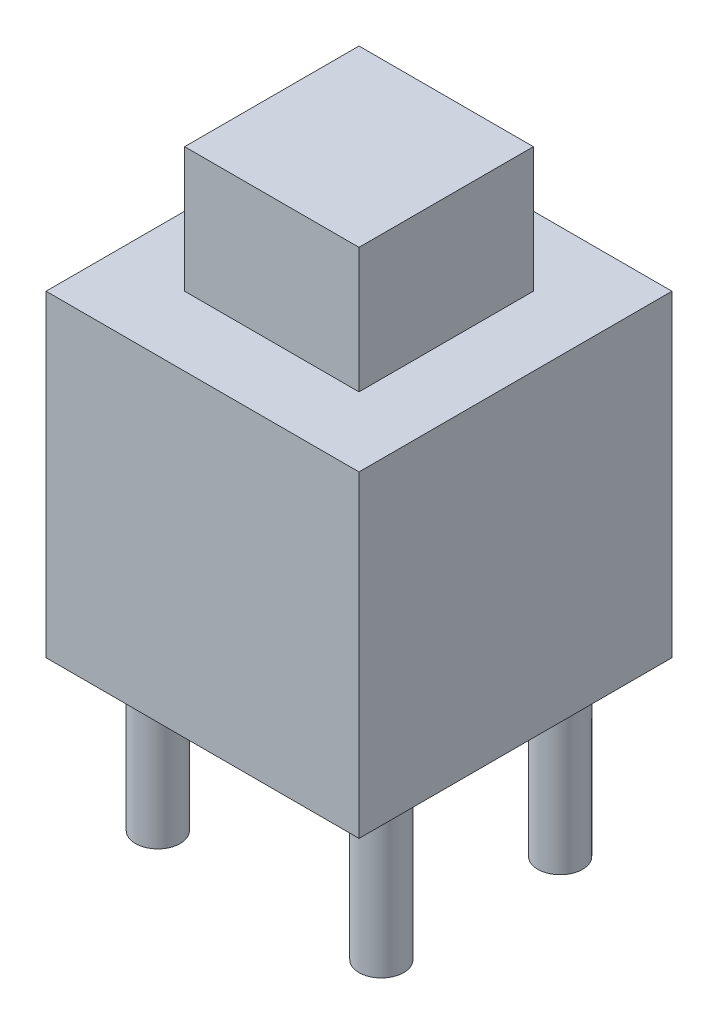
SolidWorks part; units mm, degrees
ref_plane "前视基准面" through (0, 0, 0) normal (0, 0, 1) x (1, 0, 0)
ref_plane "上视基准面" through (0, 0, 0) normal (0, 1, 0) x (1, 0, 0)
ref_plane "右视基准面" through (0, 0, 0) normal (1, 0, 0) x (0, 0, -1)
other "Configuration Table"
sketch "草图1" plane through (0, 0, 0) normal (0, 1, 0) x (1, 0, 0)
  line L1 (0, 0) -> (7, 0)
  line L2 (0, 0) -> (0, 7)
  line L3 (0, 7) -> (7, 7)
  line L4 (7, 0) -> (7, 7)
  dimension "D1" = 7
  dimension "D2" = 7
extrude "凸台-拉伸1" add sketch "草图1" along normal blind 7.1
sketch "草图2" plane through (0, 7.1, 0) normal (0, 1, 0) x (1, 0, 0)
  line L0 (3.5, 7) -> (3.5, 0) construction
  line L1 (7, 7) -> (0, 7) construction
  line L2 (0, 0) -> (7, 0) construction
  line L3 (1.55, 5.45) -> (5.45, 1.55) construction
  line L4 (1.55, 5.45) -> (5.45, 5.45)
  line L5 (1.55, 5.45) -> (1.55, 1.55)
  line L6 (1.55, 1.55) -> (5.45, 1.55)
  line L7 (5.45, 5.45) -> (5.45, 1.55)
  point P10 (3.5, 3.5)
  point P11 (0, 0)
  dimension "D1" = 3.9
extrude "凸台-拉伸2" add sketch "草图2" along normal blind 2.8
sketch "草图3" plane through (0, 0, 0) normal (0, -1, 0) x (1, 0, 0)
  line L0 (3.5, 0) -> (3.5, -7) construction
  line L1 (0, 0) -> (7, 0) construction
  line L2 (7, -7) -> (0, -7) construction
  line L3 (0, -3.5) -> (7, -3.5) construction
  line L4 (0, -7) -> (0, 0) construction
  line L5 (7, 0) -> (7, -7) construction
  circle A0 centre (1, -1.5) radius 0.5
  circle A1 centre (6, -1.5) radius 0.5
  circle A2 centre (6, -5.5) radius 0.5
  circle A3 centre (1, -5.5) radius 0.5
  point P14 (0, 0)
  point P17 (5.306, -1.1835)
  point P20 (1.7185, -5.3015)
  point P23 (5.6829, -5.2317)
  point P24 (1.7185, -5.12)
  dimension "D1" = 1
  dimension "D2" = 5
  dimension "D3" = 4
extrude "凸台-拉伸3" add sketch "草图3" along normal blind 3.6
